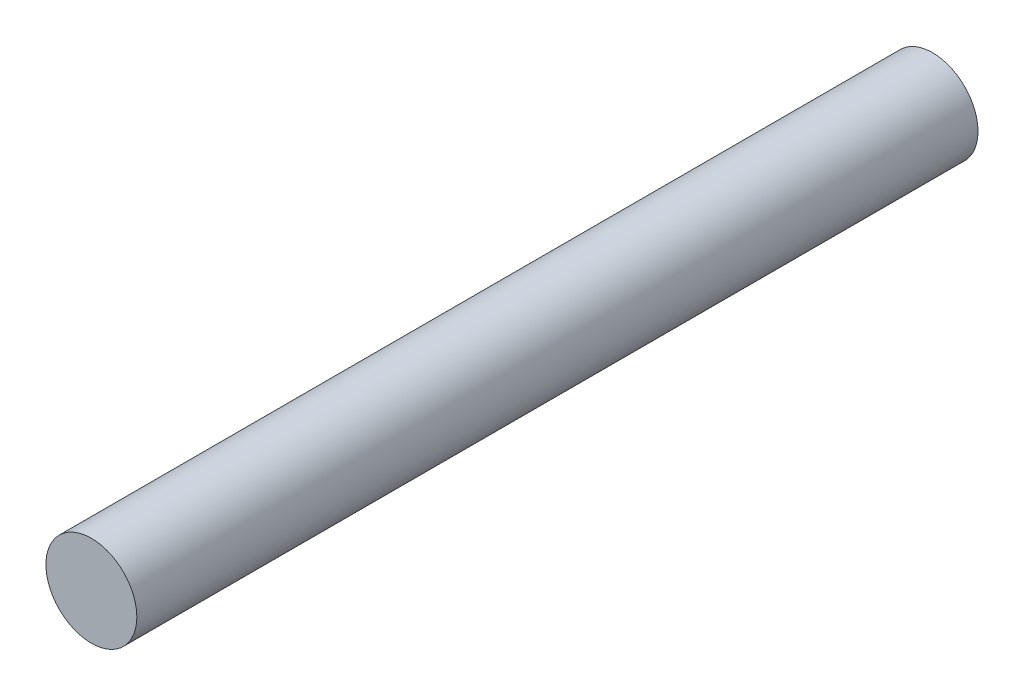
SolidWorks part; units mm, degrees
ref_plane "Front Plane" through (0, 0, 0) normal (0, 0, 1) x (1, 0, 0)
ref_plane "Top Plane" through (0, 0, 0) normal (0, 1, 0) x (1, 0, 0)
ref_plane "Right Plane" through (0, 0, 0) normal (1, 0, 0) x (0, 0, -1)
sketch "Sketch1" plane through (0, 0, 0) normal (0, 0, 1) x (1, 0, 0)
  circle A0 centre (0, 0) radius 4
  dimension "D1" = 8
extrude "Boss-Extrude1" add sketch "Sketch1" along normal blind 74
